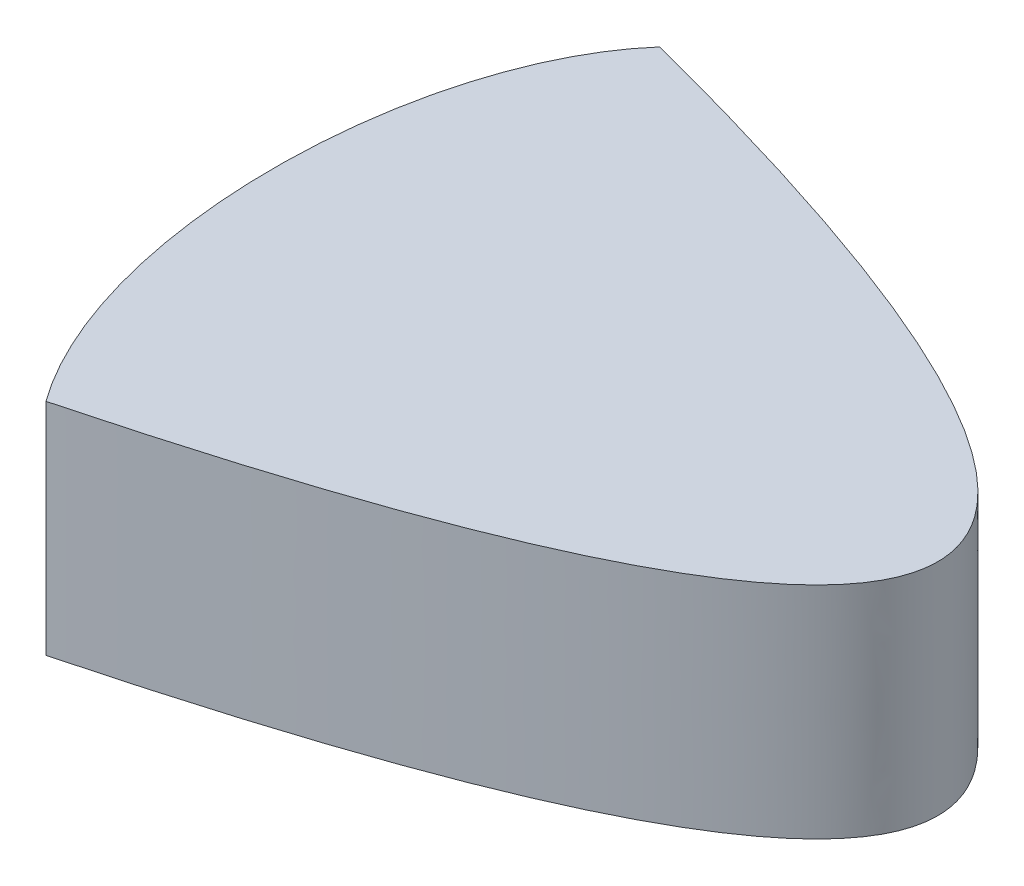
SolidWorks part; units mm, degrees
ref_plane "Front Plane" through (0, 0, 0) normal (0, 0, 1) x (1, 0, 0)
ref_plane "Top Plane" through (0, 0, 0) normal (0, 1, 0) x (1, 0, 0)
ref_plane "Right Plane" through (0, 0, 0) normal (1, 0, 0) x (0, 0, -1)
sketch "Sketch1" plane through (0, 0, 0) normal (0, 1, 0) x (1, 0, 0)
  line L0 (0, 0) -> (29.8, 0) construction
  line L1 (0, 0) -> (0, 24.3) construction
  line L2 (0, 0) -> (0, -22.5) construction
  line L3 (0, 0) -> (-86.5, 0) construction
  line L4 (-26, 0) -> (-26, 24.3) construction
  line L5 (-86.5, 0) -> (-86.5, 37.2) construction
  line L6 (-86.5, 11.6) -> (-124.6, 11.6) construction
  line L7 (-86.5, 0) -> (-86.5, -27.9) construction
  dimension "D1" = 29.8
  dimension "D2" = 24.3
  dimension "D3" = 22.5
  dimension "D4" = 26
  dimension "D5" = 86.5
  dimension "D6" = 27.9
  dimension "D7" = 37.2
  dimension "D8" = 11.6
  dimension "D9" = 38.1
sketch "Sketch2" plane through (0, 0, 0) normal (0, 1, 0) x (1, 0, 0)
  line L0 (-26, 24.3) -> (0, 24.3)
  line L1 (-124.6, 0.1449) -> (-124.6, 23.0551) construction
  line L2 (-106.5667, 37.2) -> (-66.4333, 37.2) construction
  line L3 (-42.2984, 24.3) -> (-9.7006, 24.3) construction
  line L4 (-107.4998, 37.2) -> (-65.4572, 37.2) construction
  line L5 (-64.2941, -27.9) -> (-108.7059, -27.9) construction
  line L6 (29.8, -11.2792) -> (29.8, 11.2792) construction
  line L7 (29.8, -14.0147) -> (29.8, 14.0918) construction
  spline S0 degree 3 poles (-26, 24.3) (-46.3736, 24.3) (-60.2234, 37.2) (-86.5, 37.2) knots 0 0 0 0 1 1 1 1
  spline S1 degree 3 poles (-86.5, 37.2) (-111.5833, 37.2) (-124.6, 21.1459) (-124.6, 11.6) knots 0 0 0 0 1 1 1 1
  spline S2 degree 3 poles (0, 24.3) (20.6838, 24.3847) (29.8, 14.099) (29.8, 0) knots 0 0 0 0 1 1 1 1
  spline S3 degree 3 poles (29.8, 0) (29.8, -15.9034) (12.7938, -19.6737) (0, -22.5) knots 0 0 0 0 1 1 1 1
  spline S4 degree 2 poles (-86.5, -27.9) (-58.7426, -27.9) (0, -22.5) knots 0 0 0 1 1 1
  spline S5 degree 3 poles (-124.6, 11.6) (-126.6455, -15.9296) (-96.1692, -28.4589) (-86.5, -27.9) knots 0 0 0 0 1 1 1 1
  point P0 (0, 24.3)
  point P2 (29.8, 0)
  point P4 (0, -22.5)
  point P6 (-26, 24.3)
  point P8 (-86.5, 37.2)
  point P10 (-124.6, 11.6)
  point P12 (-86.5, -27.9)
extrude "Boss-Extrude1" add sketch "Sketch2" along normal blind 10
sketch "Sketch5" plane through (0, 10, 0) normal (0, 1, 0) x (1, 0, 0)
  line L2 (0, 19.3) -> (-26, 19.3)
  line L3 (0, 19.3) -> (-26, 19.3)
  line L4 (-133.1401, 55.1699) -> (57.5258, 55.1699)
  line L5 (-133.1401, 55.1699) -> (-133.1401, -43.745)
  line L6 (-133.1401, -43.745) -> (57.5258, -43.745)
  line L7 (57.5258, 55.1699) -> (57.5258, -43.745)
  spline S10 degree 3 poles (794.3178, 2896.6346) (236.5633, 295.2684) (75.1344, 4.3942) (-36.2999, 20.219) (-38.8232, 20.7499) (-43.8284, 22.0533) (-46.3131, 22.8262) (-51.2444, 24.4704) (-53.694, 25.3411) (-58.6071, 27.0407) (-61.0707, 27.8688) (-64.8063, 28.9893) (-66.0595, 29.343) (-68.5722, 29.9962) (-69.8324, 30.2958) (-73.6263, 31.1023) (-76.1734, 31.5152) (-394.4154, 65.5197) (-1008.6606, -1988.9699) (-1423.0021, -2645.3199) knots -5.207716 -5.207716 -5.207716 -5.207716 0.125 0.125 0.25 0.25 0.375 0.375 0.5 0.5 0.625 0.625 0.6875 0.6875 0.75 0.75 0.875 0.875 16.247306 16.247306 16.247306 16.247306 only from (-26, 19.3) to (-86.5, 32.2)
  spline S11 degree 3 poles (-155.0275, 3009.7498) (283.9644, -579.3508) (39.2092, 61.7589) (-97.8181, 30.8894) (-98.6695, 30.6698) (-100.363, 30.1729) (-101.2079, 29.8946) (-103.7072, 28.973) (-105.3145, 28.249) (-108.4025, 26.5648) (-109.8852, 25.604) (-112.6954, 23.4124) (-113.9894, 22.2093) (-115.7364, 20.2177) (-116.2861, 19.5225) (-117.3076, 18.0567) (-117.7719, 17.2971) (-118.3806, 16.1123) (-118.5688, 15.7095) (-118.9104, 14.8853) (-119.0639, 14.463) (-119.321, 13.6124) (-119.4258, 13.1825) (-119.5345, 12.528) (-119.5626, 12.3083) (-119.5889, 11.9755) (-119.595, 11.8641) (-119.8529, 2.1663) (-91.4737, -13.0524) (-3067.996, 562.8701) knots -9.69525 -9.69525 -9.69525 -9.69525 0.25 0.25 0.3125 0.3125 0.375 0.375 0.5 0.5 0.625 0.625 0.75 0.75 0.8125 0.8125 0.875 0.875 0.90625 0.90625 0.9375 0.9375 0.96875 0.96875 0.984375 0.984375 0.992188 0.992188 1.660503 1.660503 1.660503 1.660503 only from (-86.5, 32.2) to (-119.6, 11.4145)
  spline S12 degree 3 poles (-3114.144, -159.344) (-75.3215, 65.211) (-118.2824, 36.1888) (-119.6695, 10.3135) (-119.7026, 9.4894) (-119.7017, 8.668) (-119.6533, 7.0291) (-119.5587, 5.9417) (-119.3168, 4.3187) (-119.2195, 3.7791) (-118.9903, 2.7027) (-118.8578, 2.164) (-118.4114, 0.5683) (-118.0496, -0.4661) (-117.2048, -2.4791) (-116.7219, -3.4578) (-115.911, -4.8862) (-115.6263, -5.3557) (-115.0287, -6.2817) (-114.7151, -6.739) (-113.0981, -8.9672) (-111.6366, -10.5868) (-109.2434, -12.8211) (-108.4118, -13.5331) (-107.1168, -14.5549) (-106.6765, -14.8883) (-105.787, -15.5353) (-105.3374, -15.8493) (-103.0661, -17.3743) (-101.1758, -18.4523) (-98.2376, -19.8702) (-97.2408, -20.3092) (-95.21, -21.1148) (-94.1746, -21.4822) (-92.0643, -22.1268) (-91.001, -22.402) (-89.3879, -22.7093) (-88.8471, -22.7942) (-88.0288, -22.8795) (-87.7547, -22.9009) (-87.3409, -22.9165) (-87.2025, -22.919) (-75.8543, -22.7912) (-57.6729, 17.6935) (-565.1077, -2984.244) knots -1.438804 -1.438804 -1.438804 -1.438804 0.015625 0.015625 0.03125 0.0625 0.0625 0.125 0.125 0.15625 0.15625 0.1875 0.1875 0.25 0.25 0.3125 0.3125 0.34375 0.34375 0.375 0.375 0.5 0.5 0.5625 0.5625 0.59375 0.59375 0.625 0.625 0.75 0.75 0.8125 0.8125 0.875 0.875 0.9375 0.9375 0.96875 0.96875 0.984375 0.984375 0.992187 0.992187 1.621629 1.621629 1.621629 1.621629 only from (-119.6, 11.4145) to (-86.6438, -22.9)
  spline S13 degree 3 poles (-743.0619, 2883.7324) (-404.1471, 44.7095) (-237.6226, -27.3739) (-72.2929, -22.6309) (-68.7098, -22.4892) (-57.9653, -21.9864) (-50.8087, -21.5494) (-36.5025, -20.5633) (-29.353, -20.0121) (442.1069, 18.8609) (896.2577, 220.25) (1524.6058, -2374.3013) knots -5.513822 -5.513822 -5.513822 -5.513822 0.125 0.125 0.25 0.25 0.5 0.5 0.75 0.75 16.991268 16.991268 16.991268 16.991268 only from (-86.6438, -22.9) to (-0.7711, -17.5498)
  spline S14 degree 3 poles (684.9632, -2932.2413) (-188.4077, 55.2091) (-72.0811, -37.5503) (8.73, -15.2186) (10.0645, -14.8145) (12.6997, -13.9014) (14.0008, -13.3934) (15.9119, -12.5052) (16.5421, -12.1879) (17.7844, -11.497) (18.3919, -11.1257) (19.5594, -10.3246) (20.1212, -9.8941) (20.9205, -9.1892) (21.1807, -8.9434) (21.6785, -8.4347) (21.9161, -8.1719) (22.5926, -7.3563) (22.9947, -6.7761) (23.5131, -5.8423) (23.6718, -5.5198) (23.9536, -4.8681) (24.0777, -4.5373) (24.4029, -3.5305) (24.5567, -2.8403) (31.3062, 45.0348) (-209.6675, 121.1409) (2725.17, -1306.3496) knots -7.13592 -7.13592 -7.13592 -7.13592 0.25 0.25 0.375 0.375 0.5 0.5 0.5625 0.5625 0.625 0.625 0.6875 0.6875 0.71875 0.71875 0.75 0.75 0.8125 0.8125 0.84375 0.84375 0.875 0.875 0.9375 0.9375 5.110249 5.110249 5.110249 5.110249 only from (-0.7711, -17.5498) to (24.8, 0)
  spline S15 degree 3 poles (3003.4514, 307.3213) (-329.5265, -207.9997) (38.0399, -68.0338) (24.2703, 5.1555) (24.0952, 5.8744) (23.7648, 6.9407) (23.6433, 7.2941) (23.3755, 7.9966) (23.2292, 8.3451) (22.7584, 9.3658) (22.3999, 10.019) (21.5892, 11.2682) (21.1362, 11.865) (19.6347, 13.56) (18.4892, 14.5137) (16.9097, 15.5257) (16.5854, 15.7195) (15.9298, 16.0859) (15.5982, 16.2589) (14.5926, 16.7499) (13.9081, 17.0401) (12.5153, 17.5579) (11.807, 17.7854) (10.3698, 18.1863) (9.6387, 18.36) (7.4366, 18.806) (5.959, 19.0045) (-85.4866, 26.721) (-201.9485, -238.1682) (23.3888, 3011.2925) knots -6.115667 -6.115667 -6.115667 -6.115667 0.125 0.125 0.1875 0.1875 0.21875 0.21875 0.25 0.25 0.3125 0.3125 0.375 0.375 0.5 0.5 0.53125 0.53125 0.5625 0.5625 0.625 0.625 0.6875 0.6875 0.75 0.75 0.875 0.875 8.448739 8.448739 8.448739 8.448739 only from (24.8, 0) to (0, 19.3)
  spline S16 degree 3 poles (-26, 19.3) (-28.6144, 19.3) (-31.1955, 19.4941) (-36.2999, 20.219) (-38.8232, 20.7499) (-43.8284, 22.0533) (-46.3131, 22.8262) (-51.2444, 24.4704) (-53.694, 25.3411) (-58.6071, 27.0407) (-61.0707, 27.8688) (-64.8063, 28.9893) (-66.0595, 29.343) (-68.5722, 29.9962) (-69.8324, 30.2958) (-73.6263, 31.1023) (-76.1734, 31.5152) (-81.3072, 32.0638) (-83.8939, 32.2) (-86.5, 32.2) knots 0 0 0 0 0.125 0.125 0.25 0.25 0.375 0.375 0.5 0.5 0.625 0.625 0.6875 0.6875 0.75 0.75 0.875 0.875 1 1 1 1
  spline S17 degree 3 poles (-86.5, 32.2) (-90.0477, 32.2) (-93.5393, 31.8534) (-97.8181, 30.8894) (-98.6695, 30.6698) (-100.363, 30.1729) (-101.2079, 29.8946) (-103.7072, 28.973) (-105.3145, 28.249) (-108.4025, 26.5648) (-109.8852, 25.604) (-112.6954, 23.4124) (-113.9894, 22.2093) (-115.7364, 20.2177) (-116.2861, 19.5225) (-117.3076, 18.0567) (-117.7719, 17.2971) (-118.3806, 16.1123) (-118.5688, 15.7095) (-118.9104, 14.8853) (-119.0639, 14.463) (-119.321, 13.6124) (-119.4258, 13.1825) (-119.5345, 12.528) (-119.5626, 12.3083) (-119.5889, 11.9755) (-119.595, 11.8641) (-119.6009, 11.64) (-119.6, 11.5271) (-119.6, 11.4145) knots 0 0 0 0 0.25 0.25 0.3125 0.3125 0.375 0.375 0.5 0.5 0.625 0.625 0.75 0.75 0.8125 0.8125 0.875 0.875 0.90625 0.90625 0.9375 0.9375 0.96875 0.96875 0.984375 0.984375 0.992188 0.992188 1 1 1 1
  spline S18 degree 3 poles (-119.6, 11.4145) (-119.6205, 11.139) (-119.64, 10.8636) (-119.6695, 10.3135) (-119.7026, 9.4894) (-119.7017, 8.668) (-119.6533, 7.0291) (-119.5587, 5.9417) (-119.3168, 4.3187) (-119.2195, 3.7791) (-118.9903, 2.7027) (-118.8578, 2.164) (-118.4114, 0.5683) (-118.0496, -0.4661) (-117.2048, -2.4791) (-116.7219, -3.4578) (-115.911, -4.8862) (-115.6263, -5.3557) (-115.0287, -6.2817) (-114.7151, -6.739) (-113.0981, -8.9672) (-111.6366, -10.5868) (-109.2434, -12.8211) (-108.4118, -13.5331) (-107.1168, -14.5549) (-106.6765, -14.8883) (-105.787, -15.5353) (-105.3374, -15.8493) (-103.0661, -17.3743) (-101.1758, -18.4523) (-98.2376, -19.8702) (-97.2408, -20.3092) (-95.21, -21.1148) (-94.1746, -21.4822) (-92.0643, -22.1268) (-91.001, -22.402) (-89.3879, -22.7093) (-88.8471, -22.7942) (-88.0288, -22.8795) (-87.7547, -22.9009) (-87.3409, -22.9165) (-87.2025, -22.919) (-86.9242, -22.9159) (-86.784, -22.9081) (-86.6438, -22.9) knots 0 0 0 0 0.015625 0.015625 0.03125 0.0625 0.0625 0.125 0.125 0.15625 0.15625 0.1875 0.1875 0.25 0.25 0.3125 0.3125 0.34375 0.34375 0.375 0.375 0.5 0.5 0.5625 0.5625 0.59375 0.59375 0.625 0.625 0.75 0.75 0.8125 0.8125 0.875 0.875 0.9375 0.9375 0.96875 0.96875 0.984375 0.984375 0.992187 0.992187 1 1 1 1
  spline S19 degree 3 poles (-86.6438, -22.9) (-83.0517, -22.9018) (-79.4639, -22.8367) (-72.2929, -22.6309) (-68.7098, -22.4892) (-57.9653, -21.9864) (-50.8087, -21.5494) (-36.5025, -20.5633) (-29.353, -20.0121) (-15.0588, -18.8335) (-7.9141, -18.2056) (-0.7711, -17.5498) knots 0 0 0 0 0.125 0.125 0.25 0.25 0.5 0.5 0.75 0.75 1 1 1 1
  spline S20 degree 3 poles (-0.7711, -17.5498) (1.9633, -16.9454) (4.6953, -16.3336) (8.73, -15.2186) (10.0645, -14.8145) (12.6997, -13.9014) (14.0008, -13.3934) (15.9119, -12.5052) (16.5421, -12.1879) (17.7844, -11.497) (18.3919, -11.1257) (19.5594, -10.3246) (20.1212, -9.8941) (20.9205, -9.1892) (21.1807, -8.9434) (21.6785, -8.4347) (21.9161, -8.1719) (22.5926, -7.3563) (22.9947, -6.7761) (23.5131, -5.8423) (23.6718, -5.5198) (23.9536, -4.8681) (24.0777, -4.5373) (24.4029, -3.5305) (24.5567, -2.8403) (24.756, -1.4273) (24.8, -0.7143) (24.8, 0) knots 0 0 0 0 0.25 0.25 0.375 0.375 0.5 0.5 0.5625 0.5625 0.625 0.625 0.6875 0.6875 0.71875 0.71875 0.75 0.75 0.8125 0.8125 0.84375 0.84375 0.875 0.875 0.9375 0.9375 1 1 1 1
  spline S21 degree 3 poles (24.8, 0) (24.8, 1.4998) (24.6799, 2.9783) (24.2703, 5.1555) (24.0952, 5.8744) (23.7648, 6.9407) (23.6433, 7.2941) (23.3755, 7.9966) (23.2292, 8.3451) (22.7584, 9.3658) (22.3999, 10.019) (21.5892, 11.2682) (21.1362, 11.865) (19.6347, 13.56) (18.4892, 14.5137) (16.9097, 15.5257) (16.5854, 15.7195) (15.9298, 16.0859) (15.5982, 16.2589) (14.5926, 16.7499) (13.9081, 17.0401) (12.5153, 17.5579) (11.807, 17.7854) (10.3698, 18.1863) (9.6387, 18.36) (7.4366, 18.806) (5.959, 19.0045) (2.9895, 19.2551) (1.4975, 19.3061) (0, 19.3) knots 0 0 0 0 0.125 0.125 0.1875 0.1875 0.21875 0.21875 0.25 0.25 0.3125 0.3125 0.375 0.375 0.5 0.5 0.53125 0.53125 0.5625 0.5625 0.625 0.625 0.6875 0.6875 0.75 0.75 0.875 0.875 1 1 1 1
  dimension "D1" = 5
extrude "Cut-Extrude2" cut sketch "Sketch5" against normal through all
sketch "Sketch3" plane through (0, 10, 0) normal (0, 1, 0) x (1, 0, 0)
  line L0 (0, 0) -> (-59.9237, 0) construction
  line L1 (0, 0) -> (-86.5, 0) construction
  line L2 (-59.9237, 0) -> (-86.5, 13.95) construction
  line L3 (-86.5, 0) -> (-86.5, 37.2) construction
  line L4 (-86.5, 13.95) -> (-86.5, -13.95) construction
  line L5 (-86.5, 0) -> (-86.5, -27.9) construction
  line L6 (-86.5, -13.95) -> (-59.9237, 0) construction
  line L9 (-140.3675, 50.6461) -> (46.6672, 50.6461)
  line L10 (-140.3675, 50.6461) -> (-140.3675, -41.0478)
  line L11 (-140.3675, -41.0478) -> (46.6672, -41.0478)
  line L13 (46.6672, 50.6461) -> (46.6672, -41.0478)
  spline S0 degree 3 poles (-86.5, -13.95) (-91.9618, -6.4228) (-91.7175, 8.0405) (-86.5, 13.95) knots 0 0 0 0 1 1 1 1
  spline S1 degree 2 poles (-86.5, 13.95) (-33.3474, 0) (-86.5, -13.95) knots 0 0 0 1 1 1
extrude "Cut-Extrude1" cut sketch "Sketch3" against normal through all
